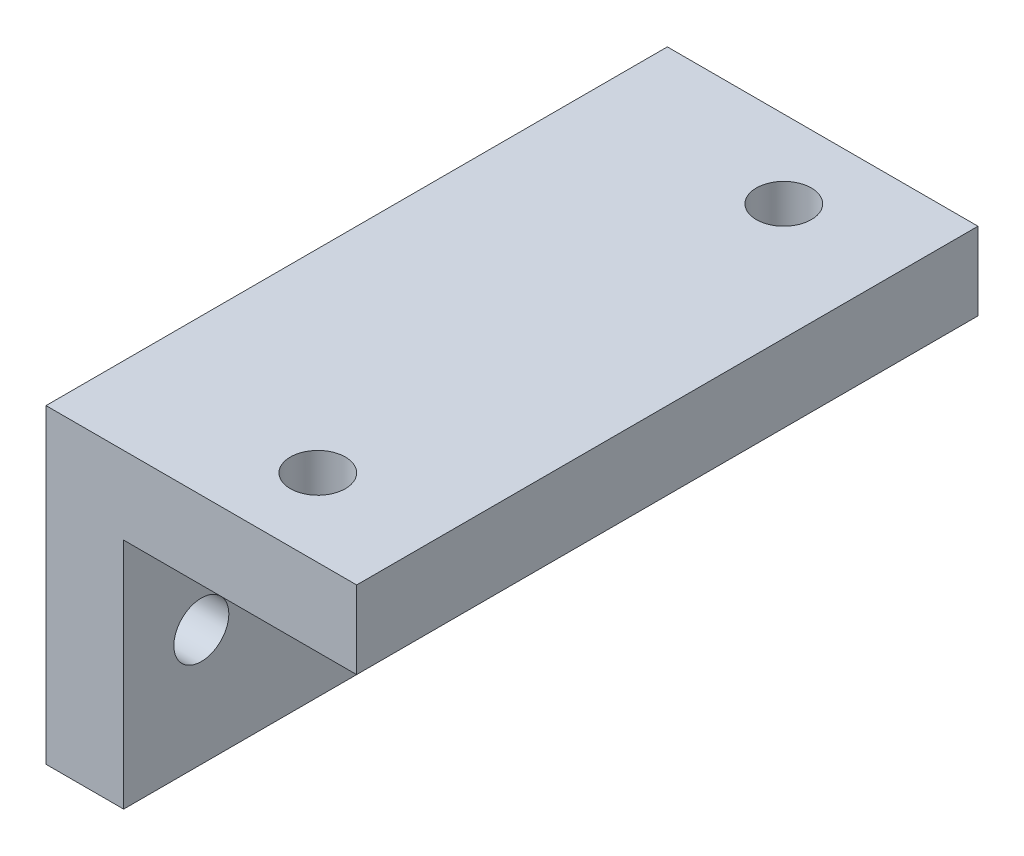
SolidWorks part; units mm, degrees
material "6061-T6 (SS)"
ref_plane "Front Plane" through (0, 0, 0) normal (0, 0, 1) x (1, 0, 0)
ref_plane "Top Plane" through (0, 0, 0) normal (0, 1, 0) x (1, 0, 0)
ref_plane "Right Plane" through (0, 0, 0) normal (1, 0, 0) x (0, 0, -1)
sketch "Sketch1" plane through (0, 0, 0) normal (0, 0, 1) x (1, 0, 0)
  line L0 (0, 0) -> (19.05, 0)
  line L1 (19.05, 0) -> (19.05, 6.35)
  line L2 (19.05, 6.35) -> (-6.35, 6.35)
  line L3 (-6.35, 6.35) -> (-6.35, -19.05)
  line L4 (-6.35, -19.05) -> (0, -19.05)
  line L5 (0, -19.05) -> (0, 0)
  dimension "D1" = 6.35
  dimension "D2" = 25.4
extrude "Boss-Extrude1" add sketch "Sketch1" along normal mid plane 50.8
hole_wizard "#8 Clearance Hole1" positions "Sketch3" profile "Sketch2" hole size "#8" standard "ANSI Inch" end condition up to next
sketch "Sketch3" plane through (0, 0, 0) normal (0, -1, 0) x (-1, 0, 0)
  line L0 (-9.525, 25.4) -> (-9.525, 50025.4) construction
  line L1 (0, 25.4) -> (-19.05, 25.4) construction
  line L2 (-19.05, 0) -> (-50019.05, 0) construction
  line L3 (-19.05, -25.4) -> (-19.05, 25.4) construction
  point P0 (-9.525, -19.05)
  point P2 (-9.525, 19.05)
  point P9 (-9.525, 25.4)
  point P14 (-19.05, 0)
  dimension "D1" = 38.1
sketch "Sketch2" plane through (9.525, 0, 19.05) normal (1, 0, 0) x (0, 0, -1)
  line L0 (0, 0) -> (0, 6.35)
  line L1 (0, 6.35) -> (2.2479, 6.35)
  line L2 (2.2479, 6.35) -> (2.2479, 0)
  line L5 (2.2479, 0) -> (0, 0)
  line L11 (0, -6.35) -> (0, 107.95) construction
  dimension "Thru Hole Dia." = 4.4958
  dimension "Thru Hole Depth" = 6.35
hole_wizard "#8 Clearance Hole2" positions "Sketch5" profile "Sketch4" hole size "#8" standard "ANSI Inch"
sketch "Sketch5" plane through (0, 0, 0) normal (1, 0, 0) x (0, 0, -1)
  line L0 (-25.4, -9.525) -> (-50025.4, -9.525) construction
  line L1 (-25.4, -19.05) -> (-25.4, 0) construction
  line L2 (0, -19.05) -> (0, 49980.95) construction
  line L3 (-25.4, -19.05) -> (25.4, -19.05) construction
  point P0 (19.05, -9.525)
  point P2 (-19.05, -9.525)
  point P9 (-25.4, -9.525)
  point P14 (0, -19.05)
  dimension "D1" = 38.1
sketch "Sketch4" plane through (0, -9.525, -19.05) normal (0, 1, 0) x (0, 0, -1)
  line L0 (0, 0) -> (0, 7.7007)
  line L1 (0, 7.7007) -> (2.2479, 6.35)
  line L2 (2.2479, 6.35) -> (2.2479, 0)
  line L5 (2.2479, 0) -> (0, 0)
  line L10 (0, 7.7007) -> (-2.2479, 6.35) construction
  line L11 (0, -6.35) -> (0, 107.95) construction
  dimension "Hole Dia." = 4.4958
  dimension "Hole Depth" = 6.35
  dimension "Drill Angle" = 118
